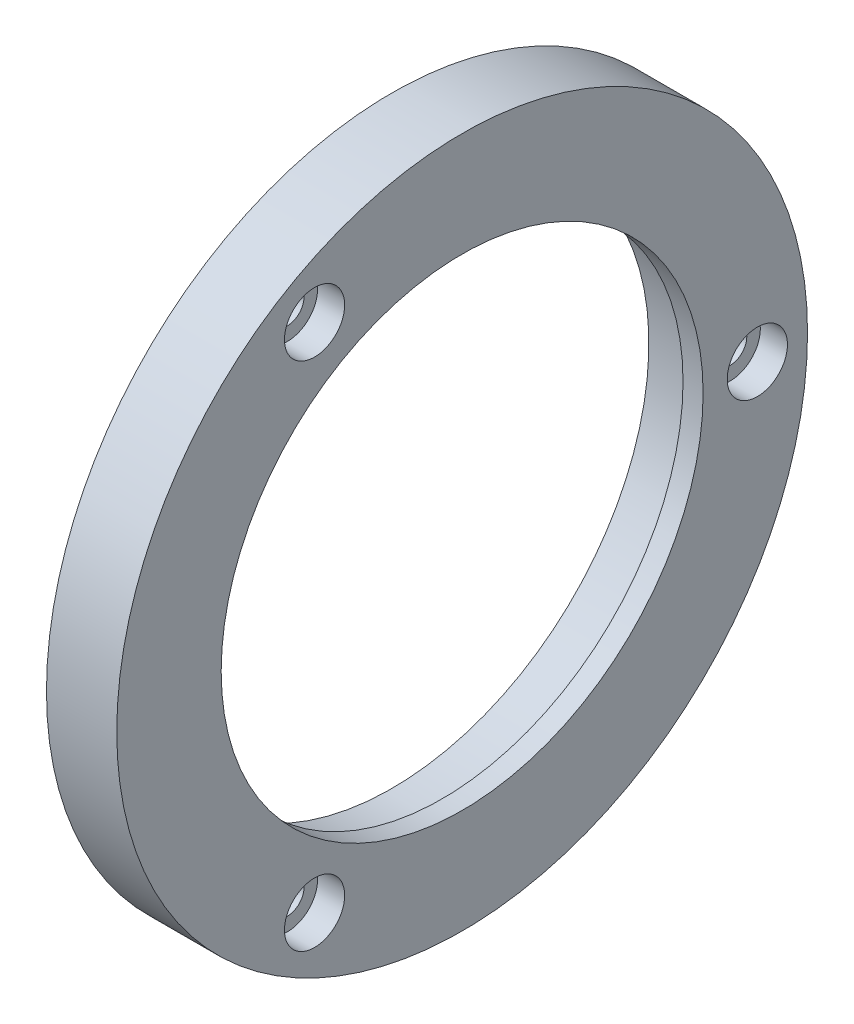
SolidWorks part; units mm, degrees
material "AISI Type 316L stainless steel"
ref_plane "Front Plane" through (0, 0, 0) normal (0, 0, 1) x (1, 0, 0)
ref_plane "Top Plane" through (0, 0, 0) normal (0, 1, 0) x (1, 0, 0)
ref_plane "Right Plane" through (0, 0, 0) normal (1, 0, 0) x (0, 0, -1)
sketch "Axial profile (mm)" plane through (0, 0, 0) normal (0, 0, 1) x (1, 0, 0)
  line L0 (-110, 0) -> (75, 0) construction
  line L1 (169.7, 25.6) -> (174.7, 25.6)
  line L2 (174.7, 25.6) -> (174.7, 24)
  line L3 (174.7, 24) -> (176.7, 24)
  line L4 (176.7, 24) -> (176.7, 34.4)
  line L5 (176.7, 34.4) -> (169.7, 34.4)
  line L6 (169.7, 34.4) -> (169.7, 25.6)
revolve "Full revolution" add sketch "Axial profile (mm)" angle 360 about L0
sketch "Sketch2" plane through (0, 0, 0) normal (1, 0, 0) x (0, 0, -1)
  circle A0 centre (29.4, 0) radius 1.65
  circle A1 centre (-14.7, 25.4611) radius 1.65
  circle A2 centre (-14.7, -25.4611) radius 1.65
extrude "Axial holes" cut sketch "Sketch2" along normal through all and the other way through all
sketch "Sketch3" plane through (0, 0, 0) normal (1, 0, 0) x (0, 0, -1)
  circle A0 centre (29.4, 0) radius 3
  circle A1 centre (-14.7, 25.4611) radius 3
  circle A2 centre (-14.7, -25.4611) radius 3
extrude "Cut-Extrude2" cut sketch "Sketch3" along normal blind 2.7 from offset 174
